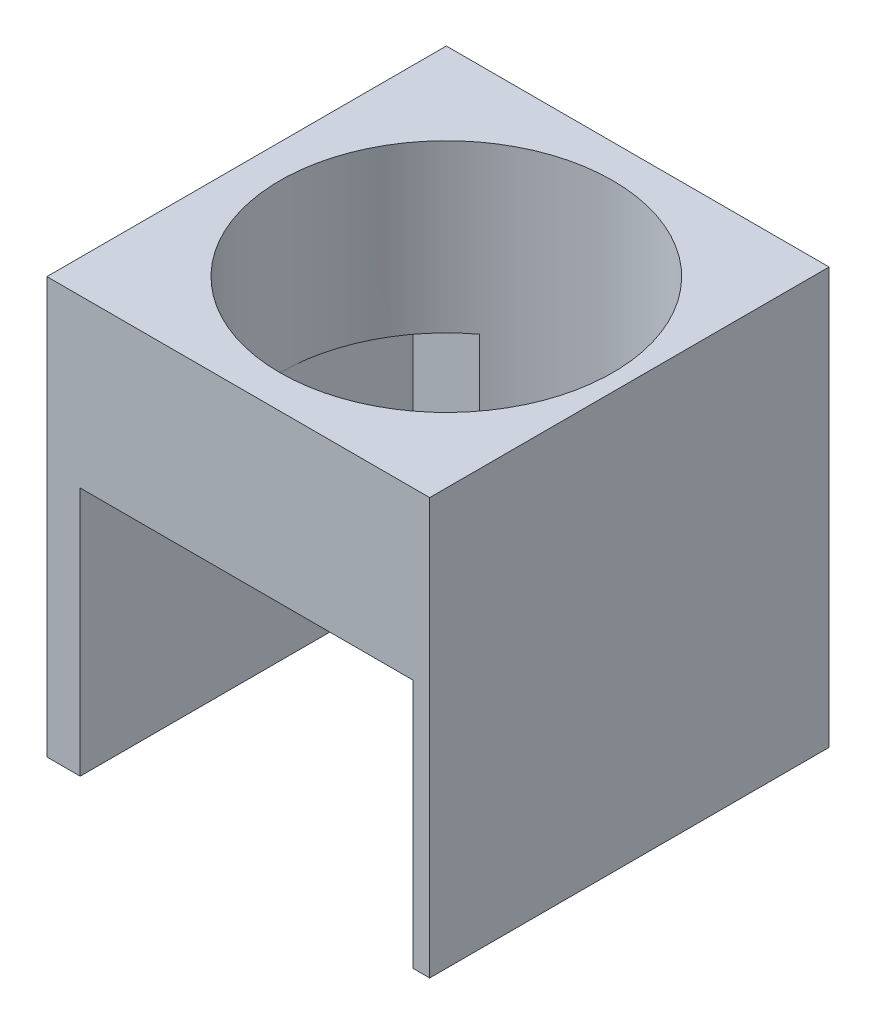
SolidWorks part; units mm, degrees
ref_plane "정면" through (0, 0, 0) normal (0, 0, 1) x (1, 0, 0)
ref_plane "윗면" through (0, 0, 0) normal (0, 1, 0) x (1, 0, 0)
ref_plane "우측면" through (0, 0, 0) normal (1, 0, 0) x (0, 0, -1)
sketch "Sketch1" plane through (0, 0, 0) normal (0, 1, 0) x (1, 0, 0)
  line L1 (0, 0) -> (670, 0)
  line L2 (0, 0) -> (0, 120)
  line L3 (0, 120) -> (670, 120)
  line L4 (670, 0) -> (670, 120)
  dimension "700" = 670
  dimension "D2" = 120
extrude "Boss-Extrude1" add sketch "Sketch1" along normal blind 530
sketch "Sketch2" plane through (0, 0, 0) normal (0, 0, 1) x (1, 0, 0)
  line L0 (0, 530) -> (0, 0) construction
  line L1 (10, 280) -> (110, 280)
  line L2 (10, 280) -> (10, 480)
  line L3 (10, 480) -> (110, 480)
  line L4 (110, 280) -> (110, 480)
  line L5 (0, 0) -> (670, 0) construction
  line L6 (120, 280) -> (120, 480)
  line L7 (120, 280) -> (220, 280)
  line L8 (220, 280) -> (220, 480)
  line L9 (120, 480) -> (220, 480)
  line L10 (230, 280) -> (230, 480)
  line L11 (230, 280) -> (330, 280)
  line L12 (330, 280) -> (330, 480)
  line L13 (230, 480) -> (330, 480)
  line L14 (340, 280) -> (340, 480)
  line L15 (340, 280) -> (440, 280)
  line L16 (440, 280) -> (440, 480)
  line L17 (340, 480) -> (440, 480)
  line L18 (450, 280) -> (450, 480)
  line L19 (450, 280) -> (550, 280)
  line L20 (550, 280) -> (550, 480)
  line L21 (450, 480) -> (550, 480)
  line L22 (560, 280) -> (560, 480)
  line L23 (560, 280) -> (660, 280)
  line L24 (660, 280) -> (660, 480)
  line L25 (560, 480) -> (660, 480)
  line L27 (10, 10) -> (660, 10)
  line L28 (10, 10) -> (10, 260)
  line L29 (10, 260) -> (660, 260)
  line L30 (660, 10) -> (660, 260)
  line L31 (0, 530) -> (670, 530) construction
  point P6 (10, 380)
  dimension "D1" = 100
  dimension "D2" = 200
  dimension "D3" = 10
  dimension "D4" = 50
  dimension "D6" = 10
  dimension "D7" = 20
  dimension "D5" = 6
extrude "Cut-Extrude1" cut sketch "Sketch2" against normal blind 100
sketch "Sketch3" plane through (0, 530, 0) normal (0, 1, 0) x (1, 0, 0)
  line L1 (670, 120) -> (0, 120) construction
  line L2 (0, 120) -> (0, 0) construction
  circle A0 centre (60, 60) radius 50
  circle A1 centre (170, 60) radius 50
  circle A2 centre (280, 60) radius 50
  circle A3 centre (390, 60) radius 50
  circle A4 centre (500, 60) radius 50
  circle A5 centre (610, 60) radius 50
  dimension "D1" = 100
  dimension "D2" = 10
  dimension "D3" = 10
  dimension "D4" = 6
extrude "Cut-Extrude2" cut sketch "Sketch3" against normal blind 260
hole_wizard "Ø12.0 (12) Diameter Hole2" positions "3DSketch1" profile "Sketch7" hole size "Ø12.0" standard "Ansi Metric"
sketch3d "3DSketch1"
  point P0 (59.7046, 270, -102.4117)
  point P2 (171.5567, 270, -102.6076)
  point P4 (280.8723, 270, -102.3969)
  point P6 (391.0687, 270, -102.7535)
  point P8 (500.7133, 270, -101.754)
  point P10 (609.5165, 270, -101.1227)
sketch "Sketch7" plane through (59.7046, 270, -102.4117) normal (1, 0, 0) x (0, 0, 1)
  line L0 (0, 0) -> (0, 33.6052)
  line L1 (0, 33.6052) -> (6, 30)
  line L2 (6, 30) -> (6, 0)
  line L5 (6, 0) -> (0, 0)
  line L10 (0, 33.6052) -> (-6, 30) construction
  line L11 (0, -6.35) -> (0, 107.95) construction
  dimension "구멍 지름" = 12
  dimension "구멍 깊이" = 30
  dimension "드릴 각도" = 118
sketch "Sketch8" plane through (0, 0, 0) normal (0, 0, 1) x (1, 0, 0)
  line L0 (660, 280) -> (660, 480) construction
  line L1 (10, 280) -> (660, 280)
  line L2 (10, 280) -> (10, 330)
  line L3 (10, 330) -> (660, 330)
  line L4 (660, 280) -> (660, 330)
  dimension "D1" = 50
extrude "Boss-Extrude2" add sketch "Sketch8" against normal blind 5
sketch "Sketch9" plane through (670, 0, 0) normal (1, 0, 0) x (0, 0, -1)
  line L0 (0, 530) -> (0, 0) construction
  line L1 (10, 10) -> (20, 10)
  line L2 (10, 10) -> (10, 260)
  line L3 (10, 260) -> (20, 260)
  line L4 (20, 10) -> (20, 260)
  line L5 (0, 0) -> (120, 0) construction
  dimension "D1" = 10
  dimension "D2" = 10
  dimension "D3" = 10
  dimension "D4" = 250
extrude "Cut-Extrude3" cut sketch "Sketch9" against normal blind 717
sketch "Sketch10" plane through (0, 10, 0) normal (0, 1, 0) x (1, 0, 0)
  line L0 (670, 120) -> (0, 120) construction
  line L1 (365, 61.9436) -> (350, 87.9243)
  line L2 (350, 87.9243) -> (320, 87.9243)
  line L3 (320, 87.9243) -> (305, 61.9436)
  line L4 (305, 61.9436) -> (320, 35.9628)
  line L5 (320, 35.9628) -> (350, 35.9628)
  line L6 (350, 35.9628) -> (365, 61.9436)
  line L7 (0, 120) -> (0, 0) construction
  circle A0 centre (335, 61.9436) radius 25.9808 construction
  dimension "D1" = 60
  dimension "D2" = 305
extrude "Cut-Extrude4" cut sketch "Sketch10" against normal blind 5
sketch "Sketch11" plane through (0, 0, -100) normal (0, 0, 1) x (1, 0, 0)
  line L0 (10, 10) -> (660, 10) construction
  line L1 (250, 10) -> (260, 10)
  line L2 (250, 10) -> (250, 110)
  line L3 (250, 110) -> (260, 110)
  line L4 (260, 10) -> (260, 110)
  line L5 (660, 10) -> (660, 260) construction
  line L6 (410, 10) -> (420, 10)
  line L7 (410, 10) -> (410, 110)
  line L8 (410, 110) -> (420, 110)
  line L9 (420, 10) -> (420, 110)
  line L10 (25, 198.4569) -> (325, 145.5588)
  line L11 (325, 145.5588) -> (325, 122.0178)
  line L12 (325, 122.0178) -> (345, 122.0178)
  line L13 (345, 122.0178) -> (345, 145.5588)
  line L14 (345, 145.5588) -> (645, 198.4569)
  line L15 (645, 198.4569) -> (25, 198.4569)
  point P18 (345, 133.7883)
  dimension "D1" = 10
  dimension "D2" = 10
  dimension "D3" = 100
  dimension "D4" = 100
  dimension "D5" = 150
  dimension "D6" = 240
  dimension "D7" = 20
  dimension "D8" = 65
  dimension "D9" = 100
  dimension "D10" = 620
  dimension "D11" = 100
extrude "Boss-Extrude3" add sketch "Sketch11" along normal blind 78 separate body
sketch "Sketch12" plane through (0, 0, -100) normal (0, 0, 1) x (1, 0, 0)
  line L0 (660, 260) -> (10, 260) construction
  line L1 (75.1986, 260) -> (95.1986, 260)
  line L2 (75.1986, 260) -> (75.1986, 230)
  line L3 (75.1986, 230) -> (95.1986, 230)
  line L4 (95.1986, 260) -> (95.1986, 230)
  line L5 (65.1986, 260) -> (65.1986, 240) construction
  line L6 (185.1986, 260) -> (185.1986, 230)
  line L7 (185.1986, 260) -> (205.1986, 260)
  line L8 (205.1986, 260) -> (205.1986, 230)
  line L9 (185.1986, 230) -> (205.1986, 230)
  line L10 (295.1986, 260) -> (295.1986, 230)
  line L11 (295.1986, 260) -> (315.1986, 260)
  line L12 (315.1986, 260) -> (315.1986, 230)
  line L13 (295.1986, 230) -> (315.1986, 230)
  line L14 (405.1986, 260) -> (405.1986, 230)
  line L15 (405.1986, 260) -> (425.1986, 260)
  line L16 (425.1986, 260) -> (425.1986, 230)
  line L17 (405.1986, 230) -> (425.1986, 230)
  line L18 (515.1986, 260) -> (515.1986, 230)
  line L19 (515.1986, 260) -> (535.1986, 260)
  line L20 (535.1986, 260) -> (535.1986, 230)
  line L21 (515.1986, 230) -> (535.1986, 230)
  line L22 (625.1986, 260) -> (625.1986, 230)
  line L23 (625.1986, 260) -> (645.1986, 260)
  line L24 (645.1986, 260) -> (645.1986, 230)
  line L25 (625.1986, 230) -> (645.1986, 230)
  dimension "D1" = 20
  dimension "D2" = 30
  dimension "D3" = 10
  dimension "D4" = 6
extrude "Cut-Extrude5" cut sketch "Sketch12" against normal blind 80
sketch "Sketch15" plane through (345, 0, 0) normal (1, 0, 0) x (0, 0, -1)
  line L0 (20, 10) -> (20, 260) construction
  line L1 (20, 121.4638) -> (50, 121.4638)
  line L2 (20, 121.4638) -> (20, 145)
  line L3 (20, 145) -> (50, 145)
  line L4 (50, 121.4638) -> (50, 145)
  line L5 (120, 530) -> (120, 0) construction
  line L6 (100, 116.0134) -> (70, 116.0134)
  line L7 (100, 116.0134) -> (100, 145)
  line L8 (100, 145) -> (70, 145)
  line L9 (70, 116.0134) -> (70, 145)
  line L10 (20, 260) -> (10, 260) construction
  dimension "D1" = 20
  dimension "D2" = 20
  dimension "D3" = 115
  dimension "D4" = 30
extrude "Cut-Extrude7" cut sketch "Sketch15" against normal blind 35
shell "Shell1" thickness 3
sketch "Sketch16" plane through (0, 122.0178, 0) normal (0, -1, 0) x (1, 0, 0)
  line L0 (345, -50) -> (325, -50) construction
  line L1 (328, -53) -> (342, -53)
  line L2 (328, -53) -> (328, -67)
  line L3 (328, -67) -> (342, -67)
  line L4 (342, -53) -> (342, -67)
  line L5 (325, -50) -> (325, -70) construction
  line L6 (345, -50) -> (345, -70) construction
  line L7 (325, -70) -> (345, -70) construction
  dimension "D1" = 3
  dimension "D2" = 3
  dimension "D3" = 3
  dimension "D4" = 3
extrude "Cut-Extrude8" cut sketch "Sketch16" against normal blind 35
sketch "Sketch17" plane through (0, 0, 0) normal (0, 0, 1) x (1, 0, 0)
  text T0 "<b>DIFF_USER</b>" font "Britannic Bold" height in points 72
extrude "Boss-Extrude4" add sketch "Sketch17" along normal blind 5
sketch "Sketch18" plane through (0, 0, 0) normal (0, 0, 1) x (1, 0, 0)
  line L0 (670, 530) -> (670, 0) construction
  line L1 (0, 0) -> (670, 0)
  line L2 (0, 0) -> (0, 280)
  line L3 (0, 280) -> (670, 280)
  line L4 (670, 0) -> (670, 280)
  dimension "D1" = 280
extrude "Cut-Extrude10" cut sketch "Sketch18" against normal blind 159
sketch "Sketch19" plane through (0, 0, 0) normal (0, 0, 1) x (1, 0, 0)
  line L0 (0, 530) -> (670, 530) construction
  line L1 (670, 280) -> (115, 280)
  line L2 (670, 280) -> (670, 530)
  line L3 (670, 530) -> (115, 530)
  line L4 (115, 280) -> (115, 530)
  line L11 (0, 530) -> (0, 280) construction
  dimension "D1" = 115
extrude "Cut-Extrude11" cut sketch "Sketch19" against normal through all both and the other way through all
sketch "Sketch20" plane through (0, 0, 0) normal (0, 0, 1) x (1, 0, 0)
  line L0 (115, 280) -> (115, 530) construction
  line L1 (0, 280) -> (115, 280)
  line L2 (0, 280) -> (0, 405)
  line L3 (0, 405) -> (115, 405)
  line L4 (115, 280) -> (115, 405)
extrude "Cut-Extrude12" cut sketch "Sketch20" against normal through all both and the other way through all
